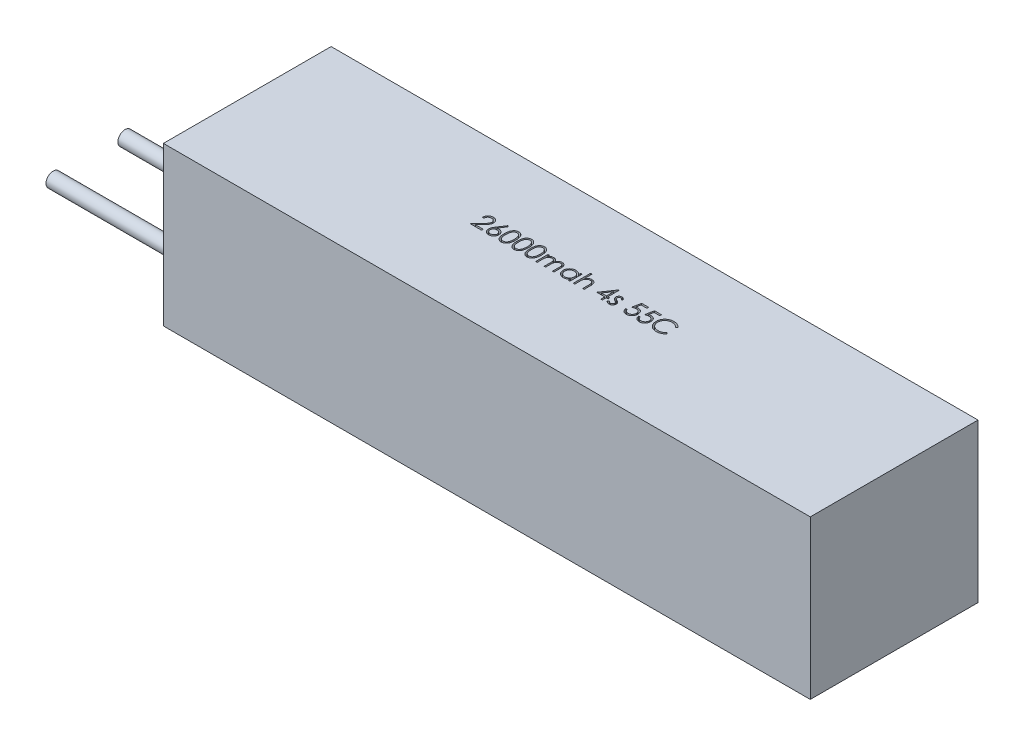
SolidWorks part; units mm, degrees
ref_plane "前视基准面" through (0, 0, 0) normal (0, 0, 1) x (1, 0, 0)
ref_plane "上视基准面" through (0, 0, 0) normal (0, 1, 0) x (1, 0, 0)
ref_plane "右视基准面" through (0, 0, 0) normal (1, 0, 0) x (0, 0, -1)
sketch "草图1" plane through (0, 0, 0) normal (0, 1, 0) x (1, 0, 0)
  line L1 (-67.5, 17.5) -> (67.5, 17.5)
  line L2 (-67.5, 17.5) -> (-67.5, -17.5)
  line L3 (-67.5, -17.5) -> (67.5, -17.5)
  line L4 (67.5, 17.5) -> (67.5, -17.5)
  line L5 (-67.5, 17.5) -> (67.5, -17.5) construction
  line L6 (-67.5, -17.5) -> (67.5, 17.5) construction
  point P0 (0, 0)
  dimension "D1" = 135
  dimension "D2" = 35
extrude "凸台-拉伸1" add sketch "草图1" along normal blind 33
sketch "草图2" plane through (-67.5, 0, 0) normal (-1, 0, 0) x (0, 0, 1)
  line L0 (-17.5, 0) -> (17.5, 0) construction
  circle A0 centre (-7.5, 5) radius 1.5
  circle A1 centre (7.5, 5) radius 1.5
  point P4 (0, 0)
  dimension "D1" = 3
  dimension "D2" = 15
  dimension "D3" = 7.5
  dimension "D4" = 5
extrude "凸台-拉伸2" add sketch "草图2" along normal blind 33
sketch "草图3" plane through (0, 33, 0) normal (0, 1, 0) x (1, 0, 0)
  text T0 "26000mah 4s 55C"
extrude "切除-拉伸1" cut sketch "草图3" against normal blind 5
